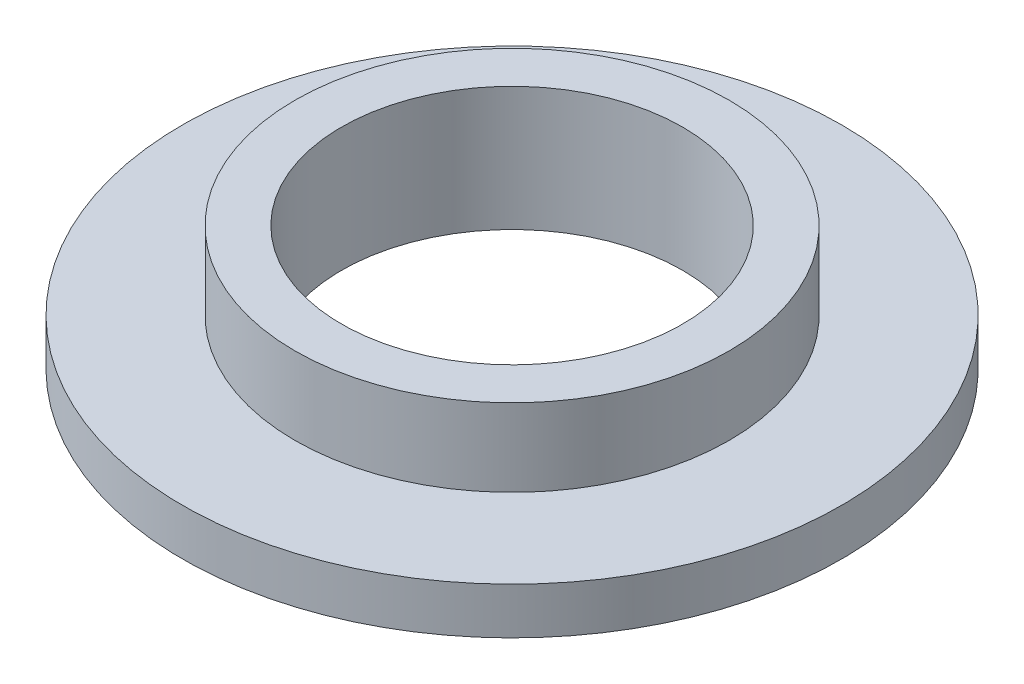
SolidWorks part; units mm, degrees
ref_plane "Front Plane" through (0, 0, 0) normal (0, 0, 1) x (1, 0, 0)
ref_plane "Top Plane" through (0, 0, 0) normal (0, 1, 0) x (1, 0, 0)
ref_plane "Right Plane" through (0, 0, 0) normal (1, 0, 0) x (0, 0, -1)
sketch "Sketch1" plane through (0, 0, 0) normal (0, 0, 1) x (1, 0, 0)
  line L0 (-2.794, 0) -> (-2.794, 2.032)
  line L1 (-2.794, 2.032) -> (-3.556, 2.032)
  line L2 (-3.556, 2.032) -> (-3.556, 0.762)
  line L3 (-3.556, 0.762) -> (-5.3975, 0.762)
  line L4 (-5.3975, 0.762) -> (-5.3975, 0)
  line L5 (-5.3975, 0) -> (-2.794, 0)
  line L6 (0, 0) -> (0, 4.8188) construction
  dimension "D1" = 2.794
  dimension "D2" = 5.3975
  dimension "D3" = 0.762
  dimension "D4" = 0.762
  dimension "D5" = 1.27
revolve "Revolve1" add sketch "Sketch1" angle 360 about L6
